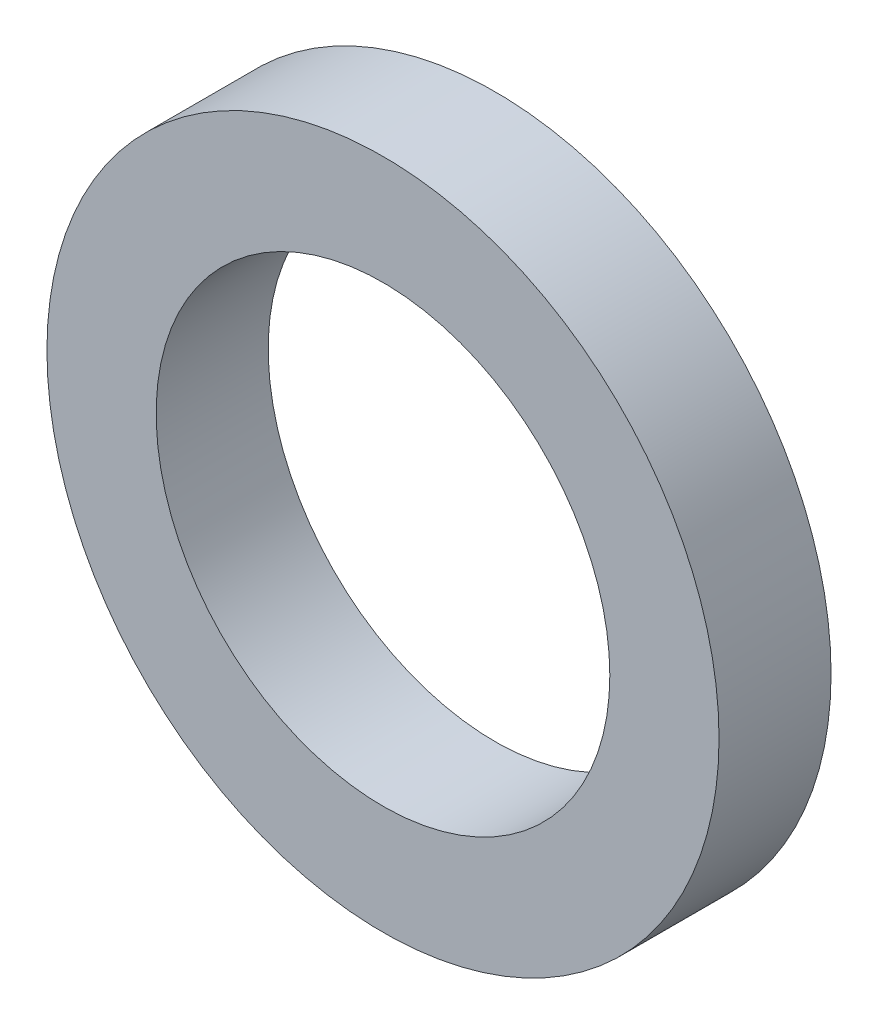
SolidWorks part; units mm, degrees
ref_plane "前视基准面" through (0, 0, 0) normal (0, 0, 1) x (1, 0, 0)
ref_plane "上视基准面" through (0, 0, 0) normal (0, 1, 0) x (1, 0, 0)
ref_plane "右视基准面" through (0, 0, 0) normal (1, 0, 0) x (0, 0, -1)
other "Configuration Table"
sketch "Profile_1" plane through (0, 0, 0) normal (0, 0, 1) x (1, 0, 0)
  circle A0 centre (0, 0) radius 6
  circle A1 centre (0, 0) radius 4.05
extrude "Ring" add sketch "Profile_1" along normal blind 2 from offset 0
